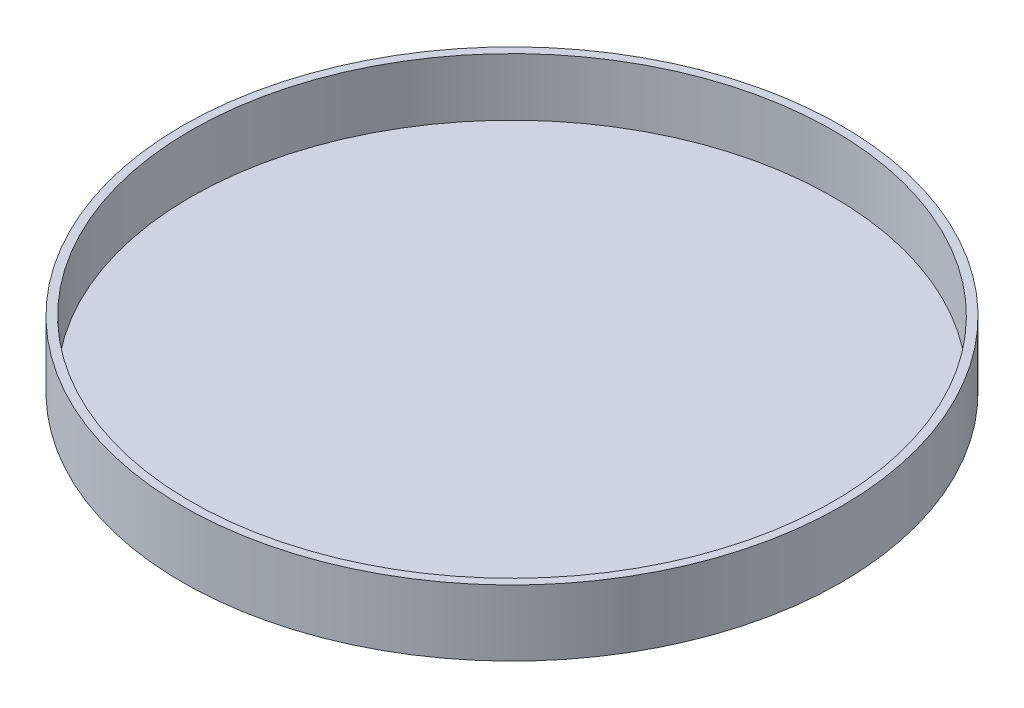
SolidWorks part; units mm, degrees
material "Ceramic Porcelain"
ref_plane "Front Plane" through (0, 0, 0) normal (0, 0, 1) x (1, 0, 0)
ref_plane "Top Plane" through (0, 0, 0) normal (0, 1, 0) x (1, 0, 0)
ref_plane "Right Plane" through (0, 0, 0) normal (1, 0, 0) x (0, 0, -1)
sketch "Sketch1" plane through (0, 0, 0) normal (0, 0, 1) x (1, 0, 0)
  line L0 (0, 0) -> (200, 0)
  line L1 (200, 0) -> (200, 40)
  line L2 (200, 40) -> (195, 40)
  line L3 (195, 40) -> (195, 5)
  line L4 (195, 5) -> (0, 5)
  line L5 (0, 5) -> (0, 0)
  dimension "D1" = 200
  dimension "D2" = 40
  dimension "D3" = 5
  dimension "D4" = 5
revolve "Revolve1" add sketch "Sketch1" angle 360 about L5
